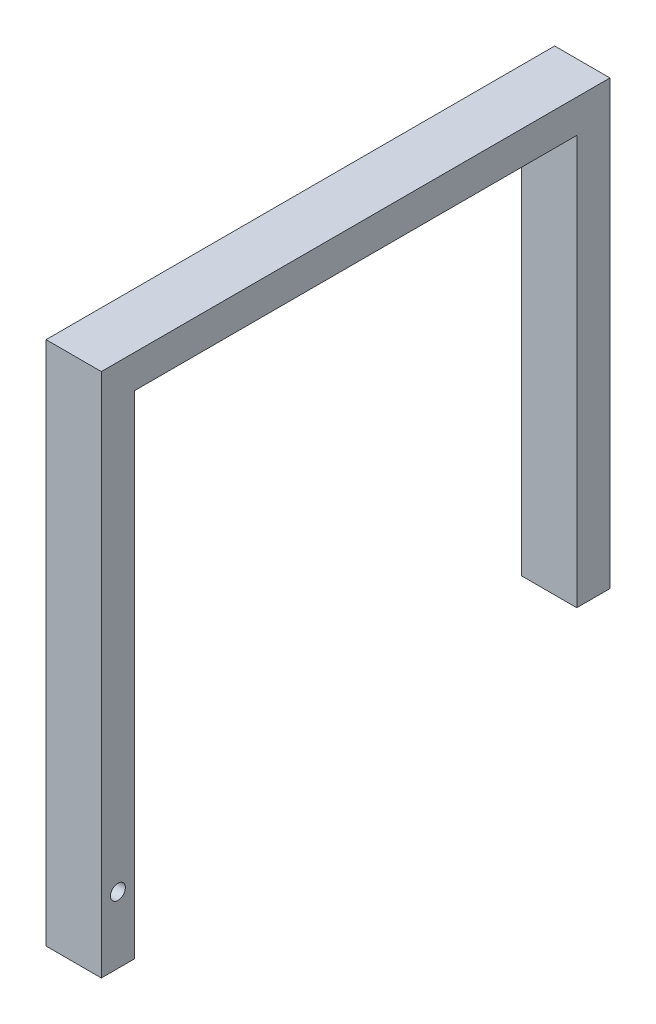
SolidWorks part; units mm, degrees
ref_plane "Front Plane" through (0, 0, 0) normal (0, 0, 1) x (1, 0, 0)
ref_plane "Top Plane" through (0, 0, 0) normal (0, 1, 0) x (1, 0, 0)
ref_plane "Right Plane" through (0, 0, 0) normal (1, 0, 0) x (0, 0, -1)
sketch "Sketch1" plane through (0, 0, 0) normal (0, 1, 0) x (1, 0, 0)
  line L1 (-5, -3) -> (5, -3)
  line L2 (-5, -3) -> (-5, 3)
  line L3 (-5, 3) -> (5, 3)
  line L4 (5, -3) -> (5, 3)
  line L5 (-5, -3) -> (5, 3) construction
  line L6 (-5, 3) -> (5, -3) construction
  point P0 (0, 0)
  dimension "D1" = 6
  dimension "D2" = 10
extrude "Boss-Extrude1" add sketch "Sketch1" along normal mid plane 80
sketch "Sketch7" plane through (0, 40, 0) normal (0, 1, 0) x (1, 0, 0)
  line L0 (-5, -3) -> (-5, -83)
  line L1 (-5, -3) -> (5, -3)
  line L2 (5, -3) -> (5, -83)
  line L3 (5, -83) -> (-5, -83)
  dimension "D1" = 80
extrude "Boss-Extrude3" add sketch "Sketch7" against normal blind 6
sketch "Sketch8" plane through (0, 40, 0) normal (0, 1, 0) x (1, 0, 0)
  line L0 (-5, -83) -> (5, -83)
  line L1 (5, -83) -> (5, -89)
  line L2 (5, -89) -> (-5, -89)
  line L3 (-5, -89) -> (-5, -83)
  dimension "D1" = 6
extrude "Boss-Extrude4" add sketch "Sketch8" against normal blind 95
sketch "Sketch9" plane through (5, 0, 0) normal (1, 0, 0) x (0, 0, -1)
  line L0 (-83, -55) -> (-83, 34) construction
  line L1 (-89, -55) -> (-83, -55) construction
  circle A0 centre (-86, -43) radius 1.35
  dimension "D2" = 2.7
  dimension "D1" = 3
  dimension "D3" = 12
extrude "Cut-Extrude3" cut sketch "Sketch9" against normal blind 80
